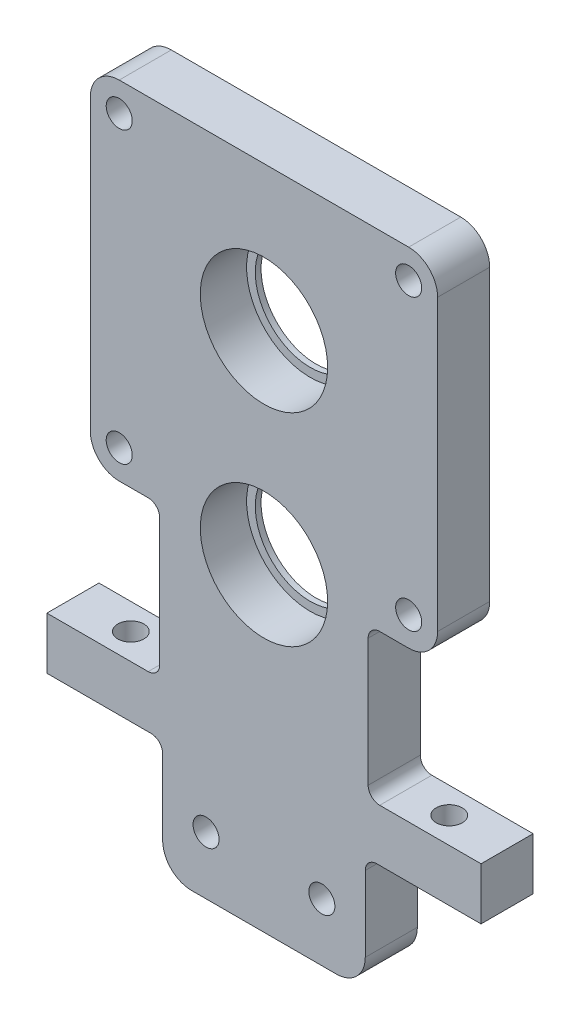
SolidWorks part; units mm, degrees
ref_plane "Plan de face" through (0, 0, 0) normal (0, 0, 1) x (1, 0, 0)
ref_plane "Plan de dessus" through (0, 0, 0) normal (0, 1, 0) x (1, 0, 0)
ref_plane "Plan de droite" through (0, 0, 0) normal (1, 0, 0) x (0, 0, -1)
sketch "Esquisse1" plane through (0, 0, 0) normal (0, 0, 1) x (1, 0, 0)
  line L1 (0, 0) -> (75, 0)
  line L2 (0, 0) -> (0, 95)
  line L3 (0, 95) -> (75, 95)
  line L4 (75, 0) -> (75, 95)
  dimension "D1" = 75
  dimension "D2" = 95
extrude "Boss.-Extru.1" add sketch "Esquisse1" along normal blind 9
sketch "Esquisse2" plane through (0, 0, 9) normal (0, 0, 1) x (1, 0, 0)
  line L0 (0, 0) -> (75, 0) construction
  line L1 (20, 0) -> (55, 0)
  line L2 (20, 0) -> (20, -20)
  line L3 (20, -20) -> (55, -20)
  line L4 (55, 0) -> (55, -20)
  line L5 (37.5, 0) -> (37.5, -20) construction
  dimension "D1" = 20
  dimension "D2" = 35
extrude "Boss.-Extru.2" add sketch "Esquisse2" against normal up to vertex (9 mm away)
sketch "Esquisse3" plane through (0, 0, 9) normal (0, 0, 1) x (1, 0, 0)
  line L0 (37.5, 70) -> (37.5, 0) construction
  line L1 (20, 0) -> (37.5, 0) construction
  line L2 (37.5, 0) -> (55, 0) construction
  line L3 (37.5, 70) -> (37.5, 95) construction
  line L4 (75, 95) -> (0, 95) construction
  circle A0 centre (37.5, 70) radius 11
  circle A1 centre (37.5, 35) radius 11
  dimension "D2" = 22
  dimension "D3" = 35
  dimension "D4" = 22
  dimension "D1" = 70
extrude "Enlèv. mat.-Extru.1" cut sketch "Esquisse3" against normal blind 8
sketch "Esquisse4" plane through (0, 0, 9) normal (0, 0, 1) x (1, 0, 0)
  circle A0 centre (37.5, 70) radius 9.5
  circle A1 centre (37.5, 70) radius 11 construction
  circle A2 centre (37.5, 35) radius 9.5
  circle A3 centre (37.5, 35) radius 11 construction
  dimension "D1" = 1.5
  dimension "D2" = 1.5
extrude "Enlèv. mat.-Extru.2" cut sketch "Esquisse4" against normal through all
sketch "Esquisse5" plane through (0, 0, 9) normal (0, 0, 1) x (1, 0, 0)
  line L0 (37.5, -20) -> (37.5, 95) construction
  line L1 (20, -20) -> (55, -20) construction
  line L2 (75, 95) -> (0, 95) construction
  line L4 (75, 9) -> (67.5, 9)
  line L5 (75, 9) -> (75, 95)
  line L6 (75, 95) -> (67.5, 95)
  line L7 (67.5, 9) -> (67.5, 95)
  line L8 (55, 0) -> (75, 0) construction
  line L9 (7.5, 9) -> (7.5, 95)
  line L10 (0, 95) -> (7.5, 95)
  line L11 (0, 9) -> (0, 95)
  line L12 (0, 9) -> (7.5, 9)
  line L13 (75, 0) -> (75, 95) construction
  point P12 (67.5, 52)
  dimension "D1" = 60
  dimension "D2" = 9
extrude "Enlèv. mat.-Extru.3" cut sketch "Esquisse5" against normal through all both and the other way through all
sketch "Esquisse8" plane through (0, 0, 9) normal (0, 0, 1) x (1, 0, 0)
  line L0 (37.5, -20) -> (37.5, -1.7723) construction
  line L1 (7.5, 9) -> (19.5, 9)
  line L2 (7.5, 9) -> (7.5, 35)
  line L3 (7.5, 35) -> (19.5, 35)
  line L4 (19.5, 9) -> (19.5, 35)
  line L5 (20, -20) -> (55, -20) construction
  line L6 (55.5, 9) -> (55.5, 35)
  line L7 (67.5, 35) -> (55.5, 35)
  line L8 (67.5, 9) -> (67.5, 35)
  line L9 (67.5, 9) -> (55.5, 9)
  dimension "D1" = 12
  dimension "D2" = 26
extrude "Enlèv. mat.-Extru.6" cut sketch "Esquisse8" against normal up to vertex
fillet "Congé1" radius 2 6 edges at (55, 0, 4.5) (20, 0, 4.5) (55.5, 35, 4.5) (55.5, 9, 4.5) (19.5, 9, 4.5) (19.5, 35, 4.5)
fillet "Congé2" radius 5 6 edges at (55, -20, 4.5) (20, -20, 4.5) (7.5, 95, 4.5) (67.5, 95, 4.5) (67.5, 35, 4.5) (7.5, 35, 4.5)
sketch "Esquisse6" plane through (0, 0, 9) normal (0, 0, 1) x (1, 0, 0)
  line L0 (20, -10) -> (55, -10) construction
  line L1 (20, -2) -> (20, -15) construction
  line L2 (55, -15) -> (55, -2) construction
  line L3 (57, 0) -> (75, 0) construction
  line L4 (37.5, -10) -> (37.5, -20) construction
  line L5 (25, -20) -> (50, -20) construction
  line L6 (7.5, 40) -> (12.5, 40) construction
  line L7 (7.5, 90) -> (7.5, 40) construction
  line L8 (12.5, 40) -> (12.5, 90) construction
  line L9 (12.5, 90) -> (7.5, 90) construction
  line L10 (17.5, 9) -> (0, 9) construction
  line L11 (62.5, 90) -> (67.5, 90) construction
  line L12 (62.5, 40) -> (62.5, 90) construction
  line L13 (67.5, 40) -> (62.5, 40) construction
  circle A0 centre (47.5, -10) radius 2.25
  circle A1 centre (27.5, -10) radius 2.25
  circle A2 centre (12.5, 90) radius 2.25
  circle A3 centre (12.5, 40) radius 2.25
  circle A4 centre (62.5, 40) radius 2.25
  circle A5 centre (62.5, 90) radius 2.25
  dimension "D2" = 4.5
  dimension "D3" = 10
  dimension "D7" = 4.5
  dimension "D1" = 10
  dimension "D4" = 31
  dimension "D5" = 50
  dimension "D6" = 5
extrude "Enlèv. mat.-Extru.4" cut sketch "Esquisse6" against normal through all
sketch "Esquisse7" plane through (0, 9, 0) normal (0, 1, 0) x (1, 0, 0)
  line L0 (10, 0) -> (10, -9) construction
  line L1 (0, 0) -> (17.5, 0) construction
  line L2 (17.5, -9) -> (0, -9) construction
  line L3 (20, -9) -> (20, 0) construction
  line L5 (37.5, -9) -> (37.5, 0) construction
  line L6 (62.5, -9) -> (12.5, -9) construction
  line L7 (62.5, 0) -> (12.5, 0) construction
  line L8 (65, 0) -> (65, -9) construction
  circle A0 centre (10, -4.5) radius 2.25
  circle A1 centre (65, -4.5) radius 2.25
  dimension "D1" = 4.5
  dimension "D2" = 10
extrude "Enlèv. mat.-Extru.5" cut sketch "Esquisse7" against normal through all
